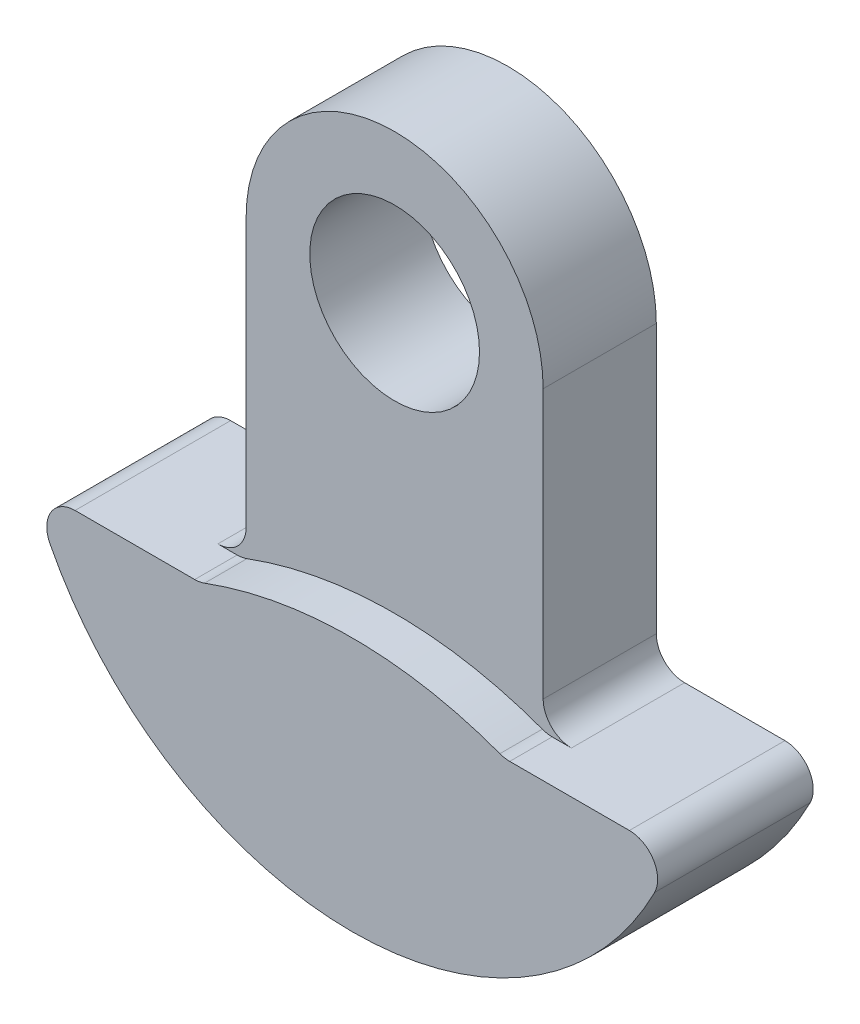
SolidWorks part; units mm, degrees
ref_plane "Plan1" through (0, 0, 0) normal (0, 0, 1) x (1, 0, 0)
ref_plane "Plan2" through (0, 0, 0) normal (0, 1, 0) x (1, 0, 0)
ref_plane "Plan3" through (0, 0, 0) normal (1, 0, 0) x (0, 0, -1)
sketch "Esquisse1" plane through (0, 0, 0) normal (0, 0, 1) x (1, 0, 0)
  line L0 (-10.5, 13) -> (-10.5, -6)
  line L1 (-19.5959, -8) -> (-12.5, -8)
  line L2 (0, 30) -> (0, -30) construction
  line L3 (10.5, 13) -> (10.5, -6)
  line L4 (19.5959, -8) -> (12.5, -8)
  arc A0 (-21.3774, -10.9091) -> (21.3774, -10.9091) centre (0, 0) ccw
  arc A1 (10.5, 13) -> (-10.5, 13) centre (0, 13) ccw
  arc A2 (-21.3774, -10.9091) -> (-19.5959, -8) centre (-19.5959, -10) cw
  arc A3 (-10.5, -6) -> (-12.5, -8) centre (-12.5, -6) cw
  arc A4 (12.5, -8) -> (10.5, -6) centre (12.5, -6) cw
  arc A5 (21.3774, -10.9091) -> (19.5959, -8) centre (19.5959, -10) ccw
  point P13 (-22.6274, -8)
  point P16 (-10.5, -8)
  point P19 (10.5, -8)
  point P22 (22.6274, -8)
  dimension "D1" = 48
  dimension "D2" = 13
  dimension "D3" = 21
  dimension "D5" = 2
  dimension "D4" = 21
extrude "Base-Extrusion" add sketch "Esquisse1" along normal blind 8
sketch "Esquisse2" plane through (0, 0, 8) normal (0, 0, 1) x (1, 0, 0)
  line L0 (-19.5959, -8) -> (-11.1355, -8)
  line L1 (11.1355, -8) -> (19.5959, -8)
  arc A0 (-21.3774, -10.9091) -> (21.3774, -10.9091) centre (0, 0) ccw
  arc A1 (-19.5959, -8) -> (-21.3774, -10.9091) centre (-19.5959, -10) ccw
  arc A2 (10.4396, -7.875) -> (-10.4396, -7.875) centre (0, -36) ccw
  arc A3 (19.5959, -8) -> (21.3774, -10.9091) centre (19.5959, -10) cw
  arc A4 (10.4396, -7.875) -> (11.1355, -8) centre (11.1355, -6) ccw
  arc A5 (-11.1355, -8) -> (-10.4396, -7.875) centre (-11.1355, -6) ccw
  dimension "D1" = 48
  dimension "D2" = 2
extrude "Boss.-Extru.1" add sketch "Esquisse2" along normal blind 3
sketch "Esquisse4" plane through (0, 0, 8) normal (0, 0, 1) x (1, 0, 0)
  circle A0 centre (0, 13) radius 6
  dimension "D1" = 12
extrude "Enlèv. mat.-Extru.1" cut sketch "Esquisse4" against normal through all
sketch "Esquisse5" plane through (0, 0, 0) normal (0, 0, -1) x (-1, 0, 0)
  circle A0 centre (0, 0) radius 5
  dimension "D1" = 10
extrude "Enlèv. mat.-Extru.2" cut sketch "Esquisse5" against normal blind 6.5
sketch "Esquisse6" plane through (0, 0, 0) normal (0, 0, -1) x (-1, 0, 0)
  circle A0 centre (0, 0) radius 6.5
  circle A1 centre (0, 0) radius 5
  dimension "D1" = 10
  dimension "D2" = 13
extrude "Boss.-Extru.2" add sketch "Esquisse6" along normal blind 1
